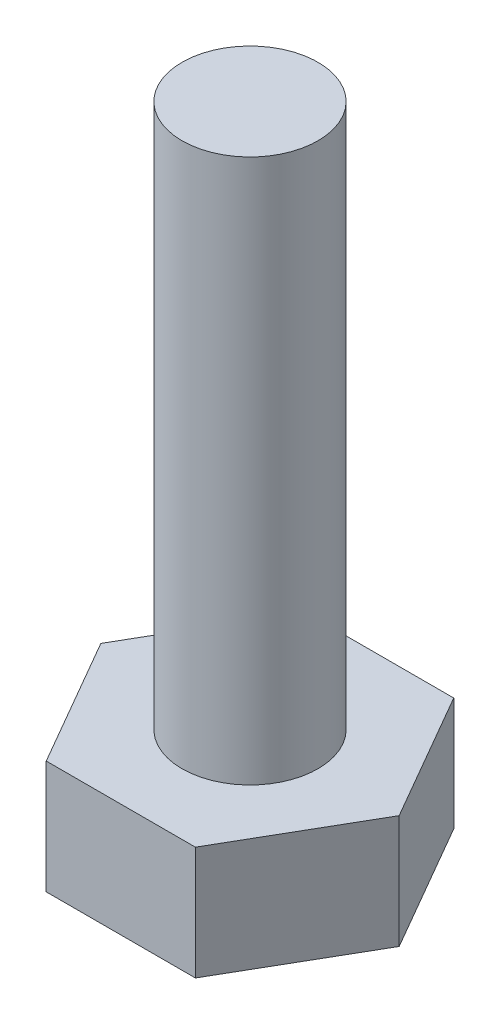
SolidWorks part; units mm, degrees
ref_plane "Front Plane" through (0, 0, 0) normal (0, 0, 1) x (1, 0, 0)
ref_plane "Top Plane" through (0, 0, 0) normal (0, 1, 0) x (1, 0, 0)
ref_plane "Right Plane" through (0, 0, 0) normal (1, 0, 0) x (0, 0, -1)
sketch "Sketch1" plane through (0, 0, 0) normal (0, 1, 0) x (1, 0, 0)
  line L1 (3.2909, 0) -> (1.6454, 2.85)
  line L2 (1.6454, 2.85) -> (-1.6454, 2.85)
  line L3 (-1.6454, 2.85) -> (-3.2909, 0)
  line L4 (-3.2909, 0) -> (-1.6454, -2.85)
  line L5 (-1.6454, -2.85) -> (1.6454, -2.85)
  line L6 (1.6454, -2.85) -> (3.2909, 0)
  circle A0 centre (0, 0) radius 2.85 construction
  dimension "D1" = 5.7
extrude "Bolt_Head" add sketch "Sketch1" along normal blind 2.5
sketch "Sketch2" plane through (0, 2.5, 0) normal (0, 1, 0) x (1, 0, 0)
  circle A0 centre (0, 0) radius 1.5
  dimension "D1" = 3
extrude "Bolt_Shaft" add sketch "Sketch2" along normal blind 12
